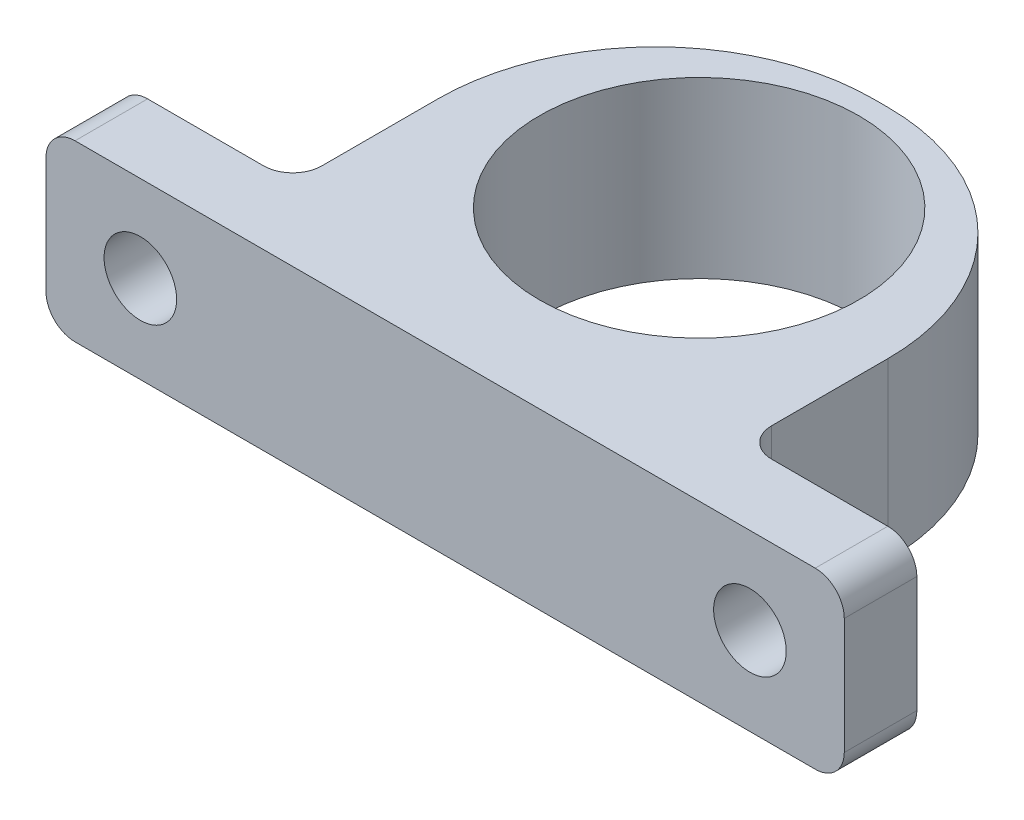
SolidWorks part; units mm, degrees
ref_plane "Front Plane" through (0, 0, 0) normal (0, 0, 1) x (1, 0, 0)
ref_plane "Top Plane" through (0, 0, 0) normal (0, 1, 0) x (1, 0, 0)
ref_plane "Right Plane" through (0, 0, 0) normal (1, 0, 0) x (0, 0, -1)
sketch "Sketch2" plane through (0, 0, 0) normal (0, 1, 0) x (1, 0, 0)
  line L0 (0, 0) -> (55, 0)
  line L1 (55, 0) -> (55, 5)
  line L2 (0, 0) -> (0, 5)
  line L3 (0, 5) -> (12, 5)
  line L4 (55, 5) -> (43, 5)
  line L5 (12, 5) -> (12, 30)
  line L6 (12, 30) -> (43, 30)
  line L7 (43, 30) -> (43, 5)
  dimension "D1" = 55
  dimension "D2" = 5
  dimension "D3" = 5
  dimension "D4" = 12
  dimension "D5" = 12
  dimension "D6" = 25
extrude "Boss-Extrude1" add sketch "Sketch2" along normal blind 12
sketch "Sketch3" plane through (0, 0, 0) normal (0, -1, 0) x (1, 0, 0)
  circle A0 centre (27.5, -17.5) radius 11
  dimension "D1" = 22
extrude "Cut-Extrude1" cut sketch "Sketch3" against normal blind 12
fillet "Fillet1" radius 15 1 edges at (43, 6, -30)
fillet "Fillet2" radius 15 1 edges at (12, 6, -30)
fillet "Fillet3" radius 2 1 edges at (12, 6, -5)
fillet "Fillet4" radius 2 1 edges at (43, 6, -5)
sketch "Sketch4" plane through (0, 0, 0) normal (0, 0, 1) x (1, 0, 0)
  circle A0 centre (48.5, 6.0341) radius 2.5
  circle A1 centre (6.5, 6.0341) radius 2.5
extrude "Cut-Extrude2" cut sketch "Sketch4" against normal blind 12
fillet "Fillet5" radius 2 1 edges at (55, 0, -2.5)
fillet "Fillet6" radius 2 1 edges at (55, 12, -2.5)
fillet "Fillet7" radius 2 1 edges at (0, 12, -2.5)
fillet "Fillet8" radius 2 1 edges at (0, 0, -2.5)
